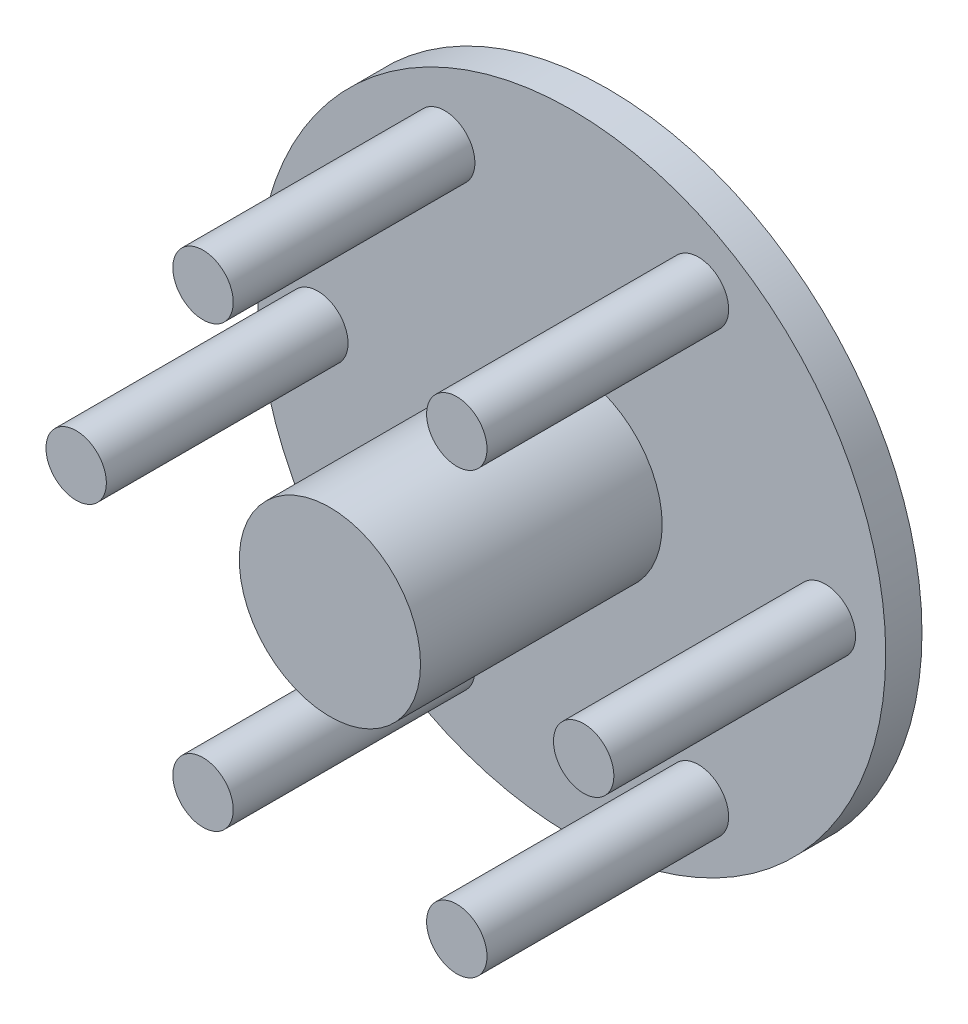
SolidWorks part; units mm, degrees
ref_plane "前视基准面" through (0, 0, 0) normal (0, 0, 1) x (1, 0, 0)
ref_plane "上视基准面" through (0, 0, 0) normal (0, 1, 0) x (1, 0, 0)
ref_plane "右视基准面" through (0, 0, 0) normal (1, 0, 0) x (0, 0, -1)
other "Configuration Table"
sketch "草图1" plane through (0, 0, 0) normal (0, 0, 1) x (1, 0, 0)
  circle A0 centre (0, 0) radius 26
  point P0 (0, 0)
  point P19 (0, 0)
  dimension "D1" = 52
extrude "凸台-拉伸1" add sketch "草图1" against normal blind 3 contours A0
sketch "草图2" plane through (0, 0, 0) normal (0, 0, 1) x (1, 0, 0)
  line L0 (0, 0) -> (-21, 0) construction
  circle A0 centre (0, 0) radius 2.5
  circle A1 centre (-21, 0) radius 2.5
  circle A2 centre (-10.5, 18.1865) radius 2.5
  circle A3 centre (10.5, 18.1865) radius 2.5
  circle A4 centre (21, 0) radius 2.5
  circle A5 centre (10.5, -18.1865) radius 2.5
  circle A6 centre (-10.5, -18.1865) radius 2.5
  point P17 (0, 0)
  dimension "D1" = 5
  dimension "D2" = 21
  dimension "D3" = 6
extrude "凸台-拉伸2" add sketch "草图2" along normal blind 20
sketch "草图3" plane through (0, 0, 0) normal (0, 0, 1) x (1, 0, 0)
  circle A0 centre (0, 0) radius 7.5
  dimension "D1" = 15
extrude "凸台-拉伸3" add sketch "草图3" along normal blind 20
